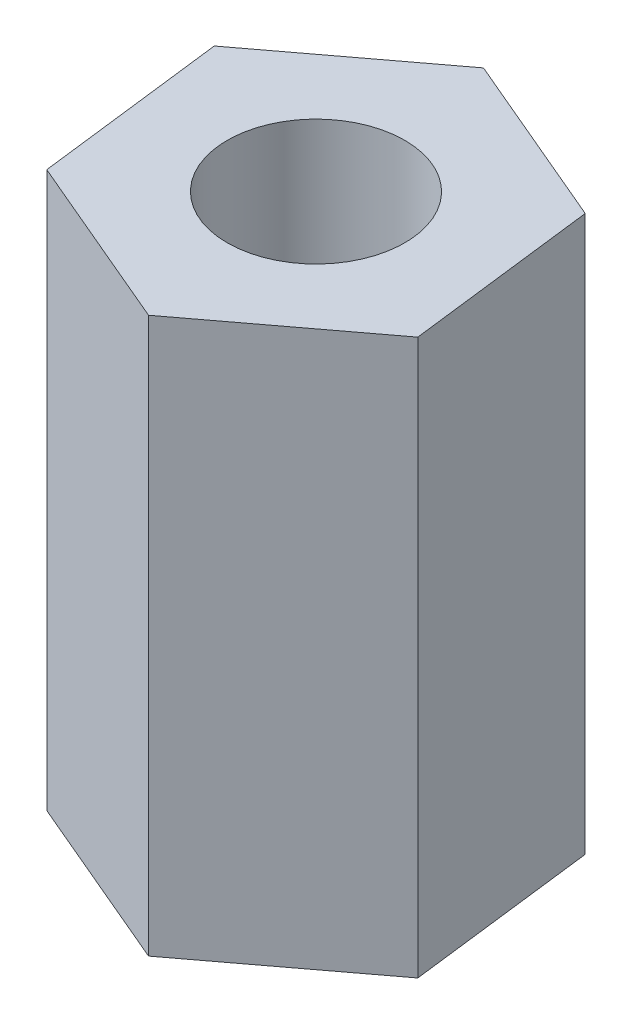
SolidWorks part; units mm, degrees
material "黄铜"
ref_plane "前视基准面" through (0, 0, 0) normal (0, 0, 1) x (1, 0, 0)
ref_plane "上视基准面" through (0, 0, 0) normal (0, 1, 0) x (1, 0, 0)
ref_plane "右视基准面" through (0, 0, 0) normal (1, 0, 0) x (0, 0, -1)
sketch "草图1" plane through (0, 0, 0) normal (0, 1, 0) x (1, 0, 0)
  line L1 (2.7672, 2.0839) -> (-0.4211, 3.4384)
  line L2 (-0.4211, 3.4384) -> (-3.1883, 1.3545)
  line L3 (-3.1883, 1.3545) -> (-2.7672, -2.0839)
  line L4 (-2.7672, -2.0839) -> (0.4211, -3.4384)
  line L5 (0.4211, -3.4384) -> (3.1883, -1.3545)
  line L6 (3.1883, -1.3545) -> (2.7672, 2.0839)
  circle A0 centre (0, 0) radius 1.6
  circle A1 centre (0, 0) radius 3 construction
  dimension "D1" = 3.2
extrude "凸台-拉伸1" add sketch "草图1" along normal blind 10
